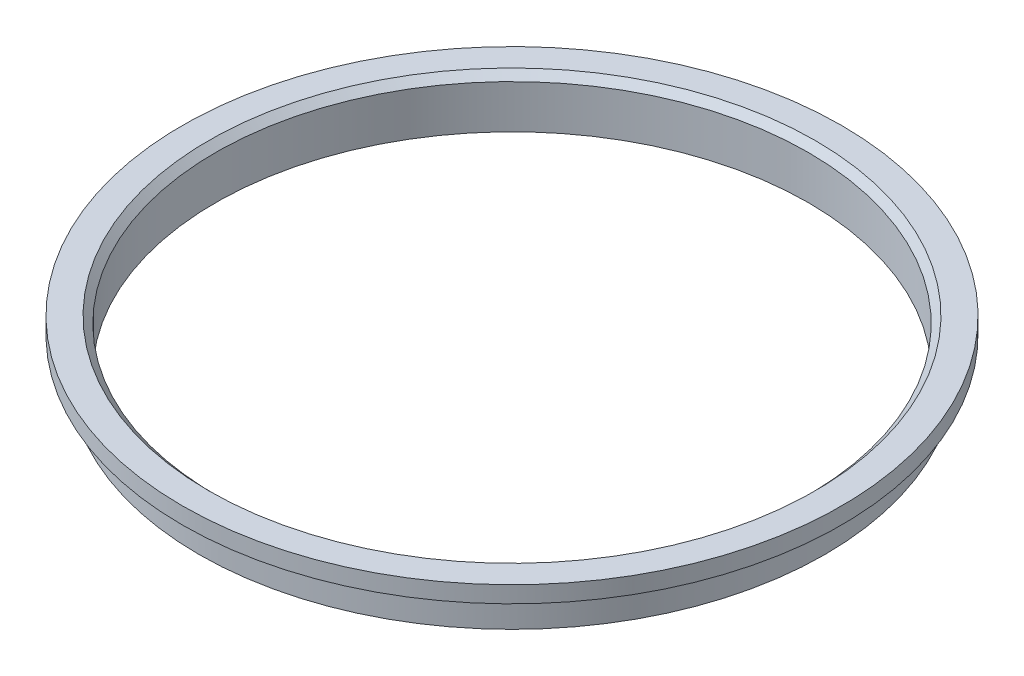
SolidWorks part; units mm, degrees
material "AISI 4340 Steel, annealed"
ref_plane "Front Plane" through (0, 0, 0) normal (0, 0, 1) x (1, 0, 0)
ref_plane "Top Plane" through (0, 0, 0) normal (0, 1, 0) x (1, 0, 0)
ref_plane "Right Plane" through (0, 0, 0) normal (1, 0, 0) x (0, 0, -1)
sketch "Sketch1" plane through (0, 0, 0) normal (0, 0, 1) x (1, 0, 0)
  line L0 (0, 0) -> (0, 24.8476) construction
  line L1 (0, 0) -> (-54.5465, 0) construction
  line L2 (-54.5465, 0) -> (-54.5465, -9.271)
  line L3 (-54.5465, -9.271) -> (-57.5945, -9.271)
  line L4 (-57.5945, -9.271) -> (-57.5945, -3.048)
  line L5 (-57.5945, -3.048) -> (-60.6425, -3.048)
  line L6 (-60.6425, -3.048) -> (-60.6425, 0)
  line L7 (-60.6425, 0) -> (-54.5465, 0)
  dimension "D1" = 6.096
  dimension "D2" = 9.271
  dimension "D3" = 3.048
  dimension "D4" = 3.048
  dimension "D5" = 57.5945
revolve "Revolve1" add sketch "Sketch1" angle 360 about L0
chamfer "Chamfer1" distance 1.27 angle 45 1 edges at (0, 0, -54.5465)
fillet "Fillet1" radius 1.5875 1 edges at (0, -3.048, -57.5945)
